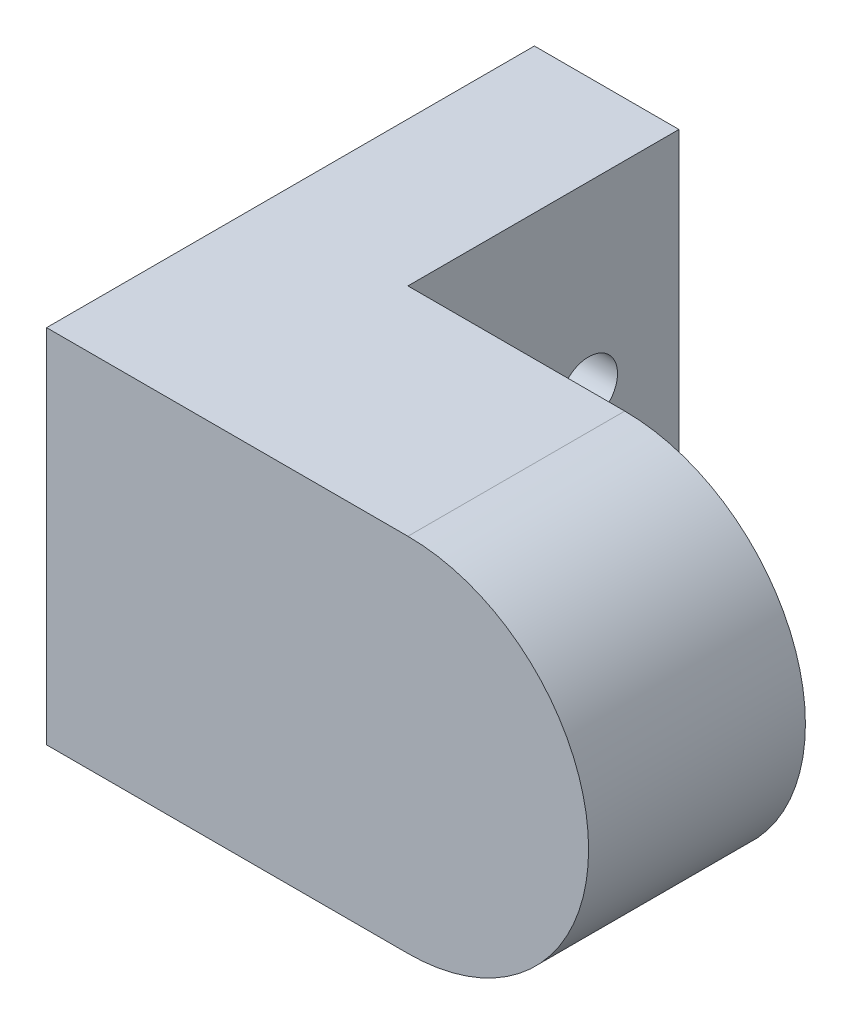
SolidWorks part; units mm, degrees
ref_plane "Plano frontal" through (0, 0, 0) normal (0, 0, 1) x (1, 0, 0)
ref_plane "Plano superior" through (0, 0, 0) normal (0, 1, 0) x (1, 0, 0)
ref_plane "Plano direito" through (0, 0, 0) normal (1, 0, 0) x (0, 0, -1)
sketch "Esboço1" plane through (0, 0, 0) normal (0, 0, 1) x (1, 0, 0)
  line L0 (0, 10) -> (-20, 10)
  line L1 (-20, 10) -> (-20, -10)
  line L2 (-20, -10) -> (0, -10)
  circle A0 centre (0, 0) radius 4
  arc A1 (0, -10) -> (0, 10) centre (0, 0) ccw
  dimension "D2" = 8
  dimension "D1" = 20
  dimension "D3" = 20
extrude "Ressalto-extrusão1" add sketch "Esboço1" along normal blind 25
sketch "Esboço2" plane through (0, 10, 0) normal (0, 1, 0) x (1, 0, 0)
  line L0 (-12, 0) -> (-12, -15)
  line L1 (0, 0) -> (-20, 0) construction
  line L2 (-12, -15) -> (10, -15)
  line L3 (10, -25) -> (10, 0) construction
  line L4 (10, -15) -> (10, 0)
  line L5 (10, 0) -> (0, 0) construction
  line L6 (10, 0) -> (-12, 0)
  line L7 (-20, -25) -> (-20, 0) construction
  line L8 (0, -25) -> (10, -25) construction
  dimension "D1" = 8
  dimension "D2" = 10
extrude "Corte-extrusão1" cut sketch "Esboço2" against normal through all both and the other way through all
sketch "Esboço3" plane through (-12, 0, 0) normal (1, 0, 0) x (0, 0, -1)
  line L0 (0, -10) -> (0, 10) construction
  circle A0 centre (-5, 0) radius 1.6
  point P4 (0, 0)
  point P5 (0, 0)
  dimension "D2" = 3.2
  dimension "D1" = 5
extrude "Corte-extrusão2" cut sketch "Esboço3" against normal blind 20
sketch "Esboço5" plane through (0, 0, 25) normal (0, 0, 1) x (1, 0, 0)
  line L3 (0, 10) -> (-20, 10)
  line L4 (-20, 10) -> (-20, -10)
  line L5 (-20, -10) -> (0, -10)
  line L6 (0, 10) -> (-20, 10)
  line L7 (-20, 10) -> (-20, -10)
  line L8 (-20, -10) -> (0, -10)
  arc A1 (0, -10) -> (0, 10) centre (0, 0) ccw
  arc A2 (0, -10) -> (0, 10) centre (0, 0) ccw
  dimension "D1" = 0
extrude "Ressalto-extrusão3" add sketch "Esboço5" along normal blind 2
